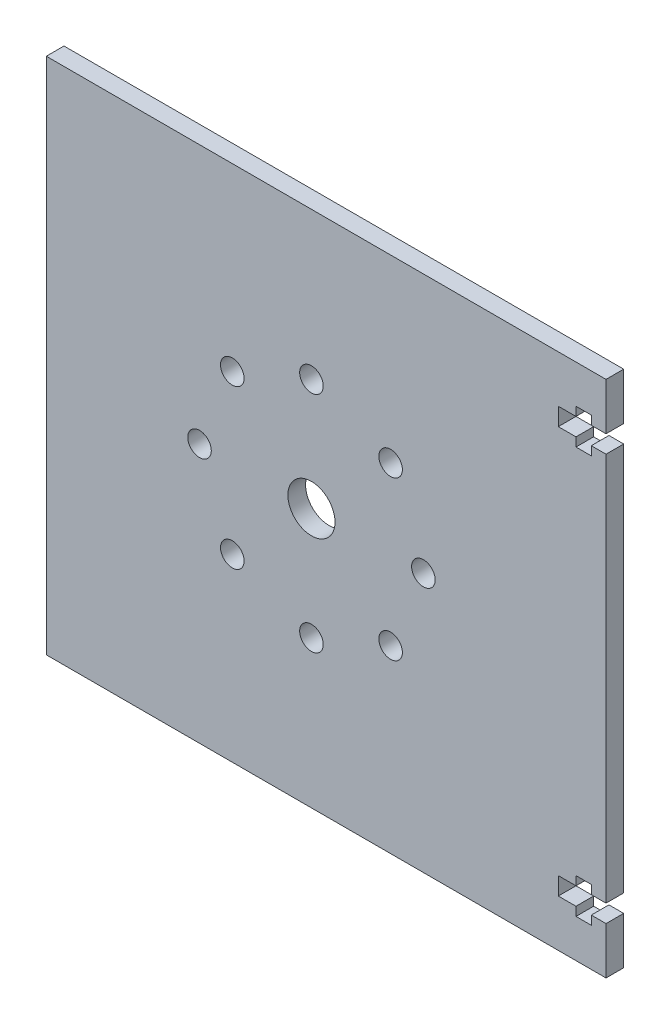
SolidWorks part; units mm, degrees
ref_plane "前视基准面" through (0, 0, 0) normal (0, 0, 1) x (1, 0, 0)
ref_plane "上视基准面" through (0, 0, 0) normal (0, 1, 0) x (1, 0, 0)
ref_plane "右视基准面" through (0, 0, 0) normal (1, 0, 0) x (0, 0, -1)
sketch "草图1" plane through (0, 0, 0) normal (0, 0, 1) x (1, 0, 0)
  line L0 (0, 0) -> (50, 0) construction
  line L1 (50, 44) -> (50, 36)
  line L2 (47.5, 36) -> (47.5, 37.5)
  line L3 (47.5, 33) -> (47.5, 31.5)
  line L4 (50, 33) -> (47.5, 33)
  line L5 (47.5, 37.5) -> (44.9, 37.5)
  line L6 (44.9, 37.5) -> (44.9, 36)
  line L7 (44.9, 36) -> (41.9, 36)
  line L8 (41.9, 33) -> (41.9, 36)
  line L9 (44.9, 33) -> (41.9, 33)
  line L10 (44.9, 31.5) -> (44.9, 33)
  line L11 (47.5, 31.5) -> (44.9, 31.5)
  line L12 (47.5, 36) -> (50, 36)
  line L13 (50, -44) -> (50, -36)
  line L14 (50, -33) -> (50, 33)
  line L15 (47.5, -33) -> (47.5, -31.5)
  line L16 (47.5, -36) -> (47.5, -37.5)
  line L17 (50, -36) -> (47.5, -36)
  line L18 (47.5, -31.5) -> (44.9, -31.5)
  line L19 (44.9, -31.5) -> (44.9, -33)
  line L20 (44.9, -33) -> (41.9, -33)
  line L21 (41.9, -36) -> (41.9, -33)
  line L22 (44.9, -36) -> (41.9, -36)
  line L23 (44.9, -37.5) -> (44.9, -36)
  line L24 (47.5, -37.5) -> (44.9, -37.5)
  line L25 (47.5, -33) -> (50, -33)
  line L26 (50, 44) -> (-45.0054, 44)
  line L27 (-45.0054, 44) -> (-45.0054, -44)
  line L28 (50, 0) -> (41.9, 0) construction
  line L29 (-45.0054, -44) -> (50, -44)
  circle A0 centre (0, 0) radius 19 construction
  circle A1 centre (0, 0) radius 4
  circle A2 centre (0, -19) radius 2
  circle A3 centre (-13.435, -13.435) radius 2
  circle A4 centre (-19, 0) radius 2
  circle A5 centre (-13.435, 13.435) radius 2
  circle A6 centre (0, 19) radius 2
  circle A7 centre (13.435, 13.435) radius 2
  circle A8 centre (19, 0) radius 2
  circle A9 centre (13.435, -13.435) radius 2
  circle A10 centre (0, 0) radius 80 construction
  dimension "D1" = 8
  dimension "D2" = 88
extrude "凸台-拉伸1" add sketch "草图1" along normal blind 3
sketch "草图2" plane through (50, 0, 0) normal (1, 0, 0) x (0, 0, -1)
  line L0 (-1.5, 36) -> (-1.5, 33)
  line L1 (-3, 36) -> (0, 36) construction
  line L2 (-3, 33) -> (0, 33) construction
  circle A0 centre (-1.5, 34.5) radius 1.5
